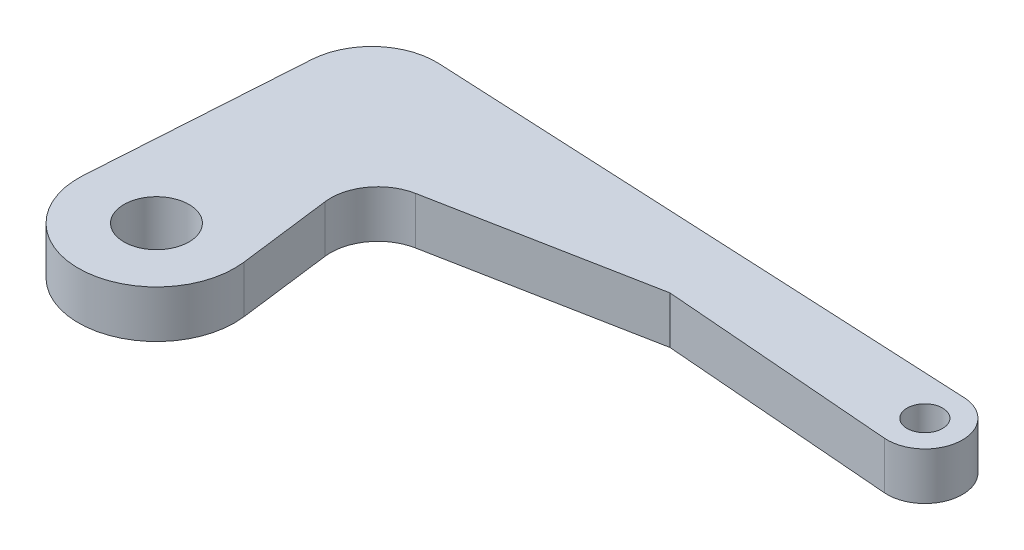
SolidWorks part; units mm, degrees
ref_plane "Front Plane" through (0, 0, 0) normal (0, 0, 1) x (1, 0, 0)
ref_plane "Top Plane" through (0, 0, 0) normal (0, 1, 0) x (1, 0, 0)
ref_plane "Right Plane" through (0, 0, 0) normal (1, 0, 0) x (0, 0, -1)
sketch "Sketch1" plane through (0, 0, 0) normal (0, 1, 0) x (1, 0, 0)
  line L0 (0, 0) -> (0, 18.2029) construction
  line L1 (0, 18.2029) -> (46.7743, 18.2029) construction
  line L2 (-5.4245, 18.5523) -> (-6.5922, 0.4246)
  line L4 (46.9277, 21.3777) -> (0.2623, 23.6323)
  line L5 (46.5215, 15.0345) -> (26.8097, 16.6072)
  line L6 (5.5542, 8.7051) -> (6.5533, 0.8316)
  line L8 (26.8097, 16.6072) -> (8.7668, 13.1366)
  circle A0 centre (0, 0) radius 2.75
  circle A1 centre (46.7743, 18.2029) radius 1.5
  arc A2 (-6.5922, 0.4246) -> (6.5533, 0.8316) centre (0, 0) ccw
  arc A3 (46.5215, 15.0345) -> (46.9277, 21.3777) centre (46.7743, 18.2029) ccw
  arc A5 (0.2623, 23.6323) -> (-5.4245, 18.5523) centre (0, 18.2029) ccw
  arc A6 (5.5542, 8.7051) -> (8.7668, 13.1366) centre (9.5223, 9.2086) cw
  point P6 (0, 0)
  point P7 (0, 0)
  point P17 (0, 0)
  point P18 (0, 0)
  point P19 (26.8097, 16.6072)
  point P21 (0, 0)
  point P22 (26.9161, 15.3562)
  point P23 (27.1024, 15.3562)
  dimension "D1" = 5.5
  dimension "D2" = 3
  dimension "D3" = 4
extrude "Boss-Extrude1" add sketch "Sketch1" along normal blind 4
